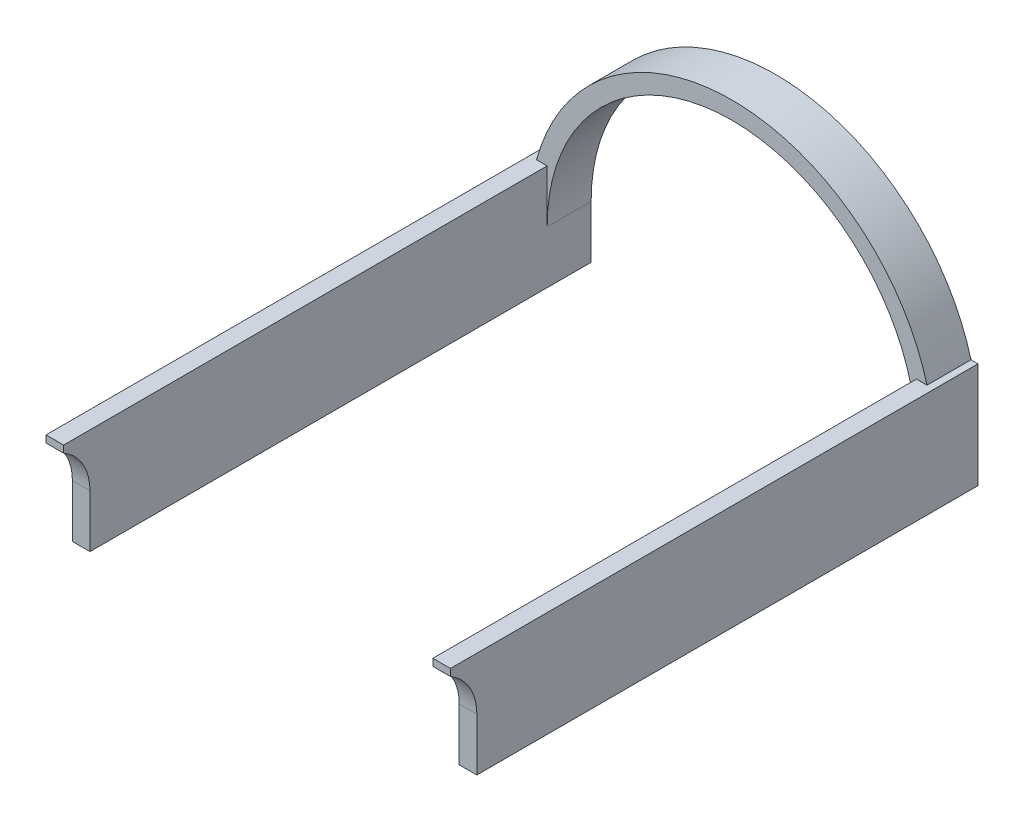
SolidWorks part; units mm, degrees
ref_plane "Front" through (0, 0, 0) normal (0, 0, 1) x (1, 0, 0)
ref_plane "Top" through (0, 0, 0) normal (0, 1, 0) x (1, 0, 0)
ref_plane "Right" through (0, 0, 0) normal (1, 0, 0) x (0, 0, -1)
sketch "草图2" plane through (0, 0, 0) normal (0, 0, 1) x (1, 0, 0)
  line L0 (-75.444, 0) -> (0, 0) construction
  line L1 (0, 0) -> (0, 80.5315) construction
  line L2 (-46, 0) -> (-42, 0)
  line L3 (42, 0) -> (46, 0)
  arc A0 (-46, 0) -> (46, 0) centre (0, 0) cw
  arc A1 (-42, 0) -> (42, 0) centre (0, 0) cw
extrude "凸台-拉伸1" add sketch "草图2" along normal blind 10
sketch "草图3" plane through (0, 0, 0) normal (0, 0, -1) x (-1, 0, 0)
  line L0 (0, 0) -> (-58.5553, 0) construction
  line L1 (-46, 12) -> (-42, 12)
  line L2 (-46, 12) -> (-46, -12)
  line L3 (-46, -12) -> (-42, -12)
  line L4 (-42, 12) -> (-42, -12)
  line L5 (46, 12) -> (42, 12)
  line L6 (46, 12) -> (46, -12)
  line L7 (46, -12) -> (42, -12)
  line L8 (42, 12) -> (42, -12)
  line L9 (0, 0) -> (0, 49.129) construction
  dimension "D1" = 4
  dimension "D2" = 46
  dimension "D3" = 24
  dimension "D4" = 12
  dimension "D5" = 4
  dimension "D6" = 24
  dimension "D7" = 12
  dimension "D8" = 46
extrude "凸台-拉伸2" add sketch "草图3" against normal blind 120
sketch "草图4" plane through (-46, 0, 0) normal (-1, 0, 0) x (0, 0, 1)
  line L0 (120, 0) -> (143.7895, 0) construction
  line L1 (120, -12) -> (120, 12) construction
  line L2 (120, 12) -> (120, -12) construction
  line L3 (114, 0) -> (114, -12)
  line L4 (120, -12) -> (0, -12) construction
  line L5 (114, -12) -> (126, -12)
  arc A0 (126, -12) -> (114, 0) centre (126, 0) ccw
  dimension "D1" = 6
extrude "切除-拉伸1" cut sketch "草图4" against normal blind 120
